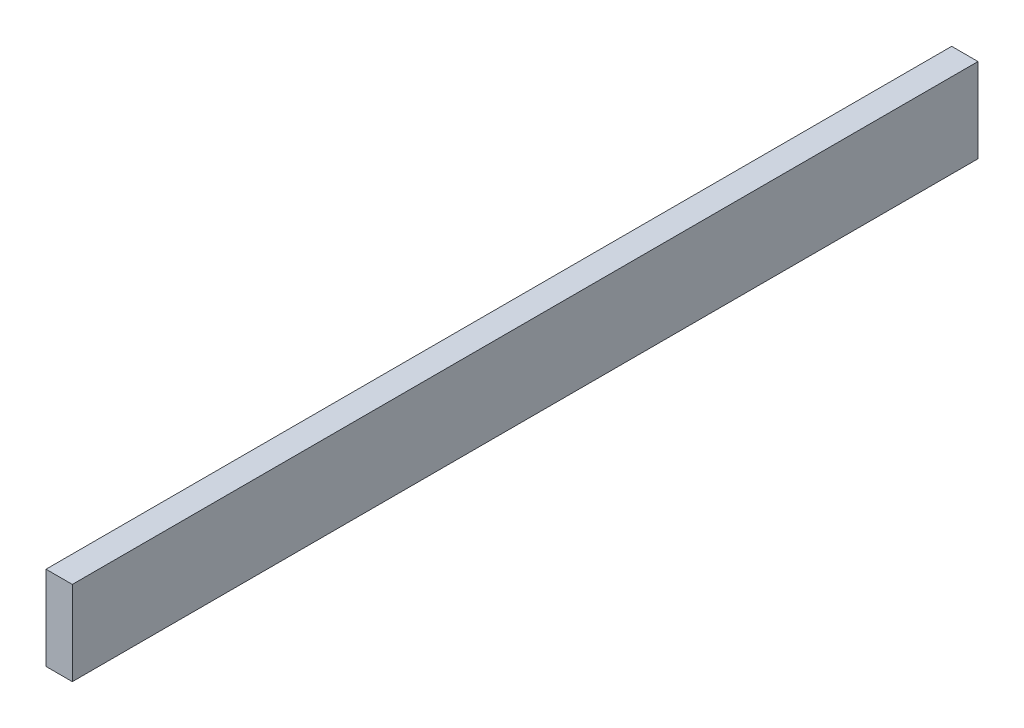
SolidWorks part; units mm, degrees
ref_plane "Alzado" through (0, 0, 0) normal (0, 0, 1) x (1, 0, 0)
ref_plane "Planta" through (0, 0, 0) normal (0, 1, 0) x (1, 0, 0)
ref_plane "Vista lateral" through (0, 0, 0) normal (1, 0, 0) x (0, 0, -1)
sketch "Croquis_faldon" plane through (0, 0, 0) normal (0, 1, 0) x (1, 0, 0)
  line L1 (-12.5, -430) -> (12.5, -430)
  line L2 (-12.5, -430) -> (-12.5, 430)
  line L3 (-12.5, 430) -> (12.5, 430)
  line L4 (12.5, -430) -> (12.5, 430)
  line L5 (-12.5, -430) -> (12.5, 430) construction
  line L6 (-12.5, 430) -> (12.5, -430) construction
  point P0 (0, 0)
  dimension "D1" = 12.5
  dimension "D2" = 430
extrude "Faldon_corto" add sketch "Croquis_faldon" along normal blind 80
